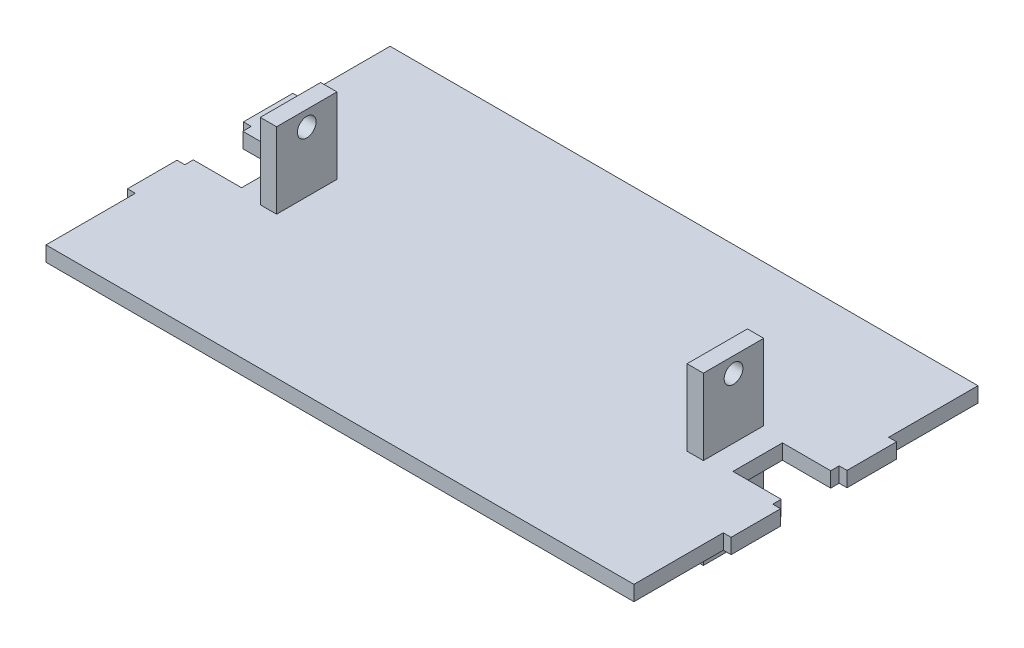
SolidWorks part; units mm, degrees
ref_plane "Front Plane" through (0, 0, 0) normal (0, 0, 1) x (1, 0, 0)
ref_plane "Top Plane" through (0, 0, 0) normal (0, 1, 0) x (1, 0, 0)
ref_plane "Right Plane" through (0, 0, 0) normal (1, 0, 0) x (0, 0, -1)
sketch "Sketch1" plane through (0, 0, 0) normal (0, 1, 0) x (1, 0, 0)
  line L0 (0, 72.39) -> (0, -72.39) construction
  line L1 (123.698, -72.39) -> (-123.698, -72.39)
  line L2 (123.698, -72.39) -> (123.698, -34.798)
  line L3 (123.698, 72.39) -> (-123.698, 72.39)
  line L4 (-123.698, -72.39) -> (-123.698, -34.798)
  line L5 (123.698, -72.39) -> (-123.698, 72.39) construction
  line L6 (123.698, 72.39) -> (-123.698, -72.39) construction
  line L7 (123.698, 10.414) -> (103.378, 10.414)
  line L9 (123.698, -10.414) -> (103.378, -10.414)
  line L10 (103.378, 10.414) -> (103.378, -10.414)
  line L13 (-123.698, -10.414) -> (-103.378, -10.414)
  line L14 (-103.378, 10.414) -> (-103.378, -10.414)
  line L15 (-123.698, 10.414) -> (-103.378, 10.414)
  line L17 (-126.9885, 0) -> (127.0115, 0) construction
  line L18 (-123.698, 13.97) -> (-127, 13.97)
  line L20 (-123.698, 34.798) -> (-127, 34.798)
  line L21 (-127, 13.97) -> (-127, 34.798)
  line L22 (-123.698, -34.798) -> (-127, -34.798)
  line L23 (-127, -13.97) -> (-127, -34.798)
  line L24 (-123.698, -13.97) -> (-127, -13.97)
  line L27 (123.698, -13.97) -> (127, -13.97)
  line L28 (127, -13.97) -> (127, -34.798)
  line L29 (123.698, -34.798) -> (127, -34.798)
  line L30 (123.698, 34.798) -> (127, 34.798)
  line L31 (127, 13.97) -> (127, 34.798)
  line L32 (123.698, 13.97) -> (127, 13.97)
  line L34 (-123.698, 34.798) -> (-123.698, 72.39)
  line L35 (-123.698, -13.97) -> (-123.698, -10.414)
  line L36 (123.698, 34.798) -> (123.698, 72.39)
  line L37 (123.698, -13.97) -> (123.698, -10.414)
  line L38 (-123.698, 10.414) -> (-123.698, 13.97)
  line L39 (123.698, 10.414) -> (123.698, 13.97)
  point P0 (0, 0)
  point P6 (127, 0)
  dimension "D1" = 247.396
  dimension "D2" = 144.78
  dimension "D3" = 20.828
  dimension "D5" = 3.302
  dimension "D6" = 20.828
  dimension "D4" = 20.32
  dimension "D7" = 3.556
  dimension "D8" = 3.556
  dimension "D9" = 3.556
  dimension "D10" = 3.556
  dimension "D11" = 37.592
  dimension "D12" = 20.828
  dimension "D13" = 37.592
extrude "Boss-Extrude1" add sketch "Sketch1" along normal mid plane 6.35
sketch "Sketch2" plane through (0, 0, 0) normal (0, 1, 0) x (1, 0, 0)
  line L0 (-103.378, 10.414) -> (-103.378, -10.414) construction
  line L1 (86.36, -12.7) -> (93.218, -12.7)
  line L2 (86.36, -12.7) -> (86.36, 12.7)
  line L3 (86.36, 12.7) -> (93.218, 12.7)
  line L4 (93.218, -12.7) -> (93.218, 12.7)
  line L5 (86.36, -12.7) -> (93.218, 12.7) construction
  line L6 (86.36, 12.7) -> (93.218, -12.7) construction
  line L9 (-86.36, -12.7) -> (-86.36, 12.7)
  line L10 (-86.36, 12.7) -> (-93.218, 12.7)
  line L11 (-93.218, -12.7) -> (-93.218, 12.7)
  line L12 (-86.36, -12.7) -> (-93.218, -12.7)
  line L13 (103.378, -10.414) -> (103.378, 10.414) construction
  point P0 (89.789, 0)
  point P10 (103.378, 0)
  dimension "D1" = 10.16
  dimension "D2" = 10.16
  dimension "D3" = 25.4
  dimension "D4" = 25.4
  dimension "D5" = 6.858
  dimension "D6" = 6.858
  dimension "D7" = 6.858
extrude "Boss-Extrude2" add sketch "Sketch2" along normal mid plane 70.104
sketch "Sketch3" plane through (-93.218, 0, 0) normal (-1, 0, 0) x (0, 0, 1)
  line L0 (12.7, 3.175) -> (-12.7, 3.175) construction
  line L1 (12.7, -3.175) -> (-12.7, -3.175) construction
  circle A0 centre (0, 28.575) radius 3.937
  circle A1 centre (0, -28.575) radius 3.937
  dimension "D1" = 7.874
  dimension "D2" = 7.874
  dimension "D3" = 25.4
  dimension "D4" = 25.4
extrude "Cut-Extrude1" cut sketch "Sketch3" against normal through all both and the other way through all
equation "\"length\"=9.74"
equation "\"width\"=5.7"
equation "\"height\"= 0.25"
equation "\"D1@Sketch1\"=\"length\""
equation "\"D2@Sketch1\"=\"width\""
equation "\"eyebolt width\"= 0.82"
equation "\"eyebolt length\"= 0.8"
equation "\"D3@Sketch1\"=\"eyebolt width\""
equation "\"D4@Sketch1\"=\"eyebolt length\""
equation "\"lead screw holder height\"= 2.76"
equation "\"lead screw diameter\"= 0.31"
equation "\"D1@Sketch3\"=\"lead screw diameter\""
equation "\"distance from holders to board\"=0.4"
equation "\"D2@Sketch3\"=\"lead screw diameter\""
